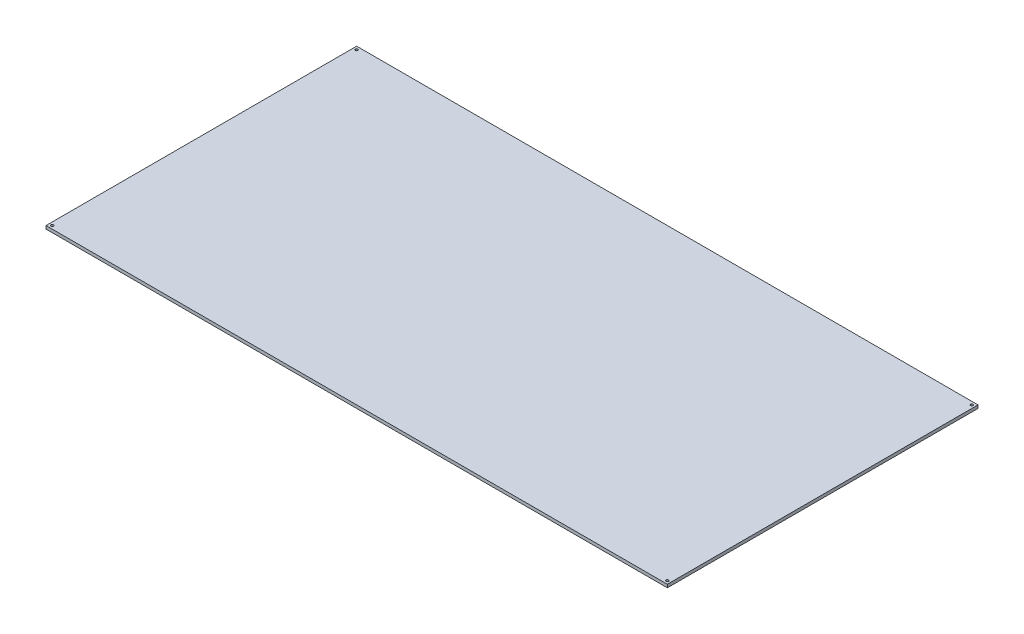
SolidWorks part; units mm, degrees
ref_plane "前视基准面" through (0, 0, 0) normal (0, 0, 1) x (1, 0, 0)
ref_plane "上视基准面" through (0, 0, 0) normal (0, 1, 0) x (1, 0, 0)
ref_plane "右视基准面" through (0, 0, 0) normal (1, 0, 0) x (0, 0, -1)
sketch "草图1" plane through (0, 0, 0) normal (0, 1, 0) x (1, 0, 0)
  line L1 (-971.7056, 454.7972) -> (1028.2944, 454.7972)
  line L2 (-971.7056, 454.7972) -> (-971.7056, -545.2028)
  line L3 (-971.7056, -545.2028) -> (1028.2944, -545.2028)
  line L4 (1028.2944, 454.7972) -> (1028.2944, -545.2028)
  dimension "D1" = 2000
  dimension "D2" = 1000
extrude "凸台-拉伸1" add sketch "草图1" along normal blind 10
sketch "草图2" plane through (0, 10, 0) normal (0, 1, 0) x (1, 0, 0)
  line L0 (-971.7056, 454.7972) -> (-971.7056, -545.2028) construction
  line L1 (1028.2944, 454.7972) -> (-971.7056, 454.7972) construction
  circle A0 centre (-961.7056, 444.7972) radius 4
  circle A1 centre (1018.2944, 444.7972) radius 4
  circle A2 centre (1018.2944, -535.2028) radius 4
  circle A3 centre (-961.7056, -535.2028) radius 4
  dimension "D1" = 10
  dimension "D3" = 8
  dimension "D2" = 10
  dimension "D4" = 2
  dimension "D5" = 2
extrude "切除-拉伸1" cut sketch "草图2" against normal blind 10
